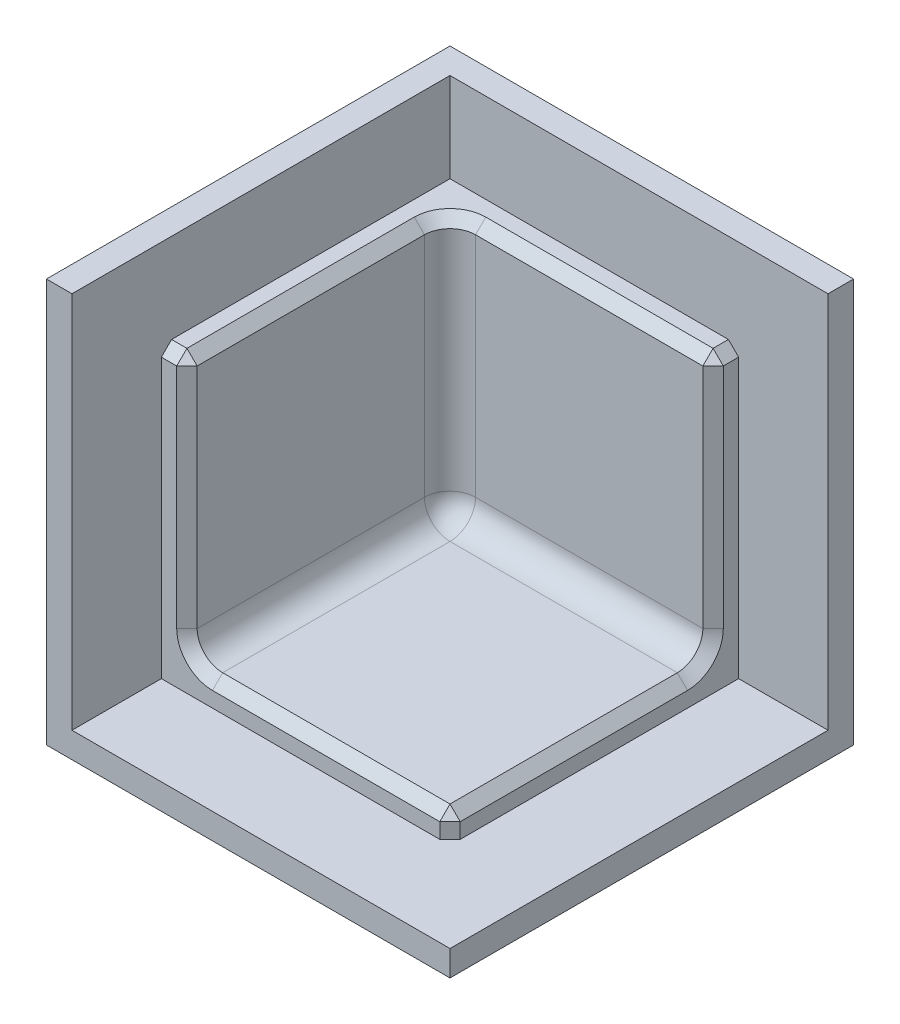
SolidWorks part; units mm, degrees
ref_plane "Plan de face" through (0, 0, 0) normal (0, 0, 1) x (1, 0, 0)
ref_plane "Plan de dessus" through (0, 0, 0) normal (0, 1, 0) x (1, 0, 0)
ref_plane "Plan de droite" through (0, 0, 0) normal (1, 0, 0) x (0, 0, -1)
sketch "Esquisse1" plane through (0, 0, 0) normal (0, 1, 0) x (1, 0, 0)
  line L1 (-7.9, 7.9) -> (7.9, 7.9)
  line L2 (-7.9, 7.9) -> (-7.9, -7.9)
  line L3 (-7.9, -7.9) -> (7.9, -7.9)
  line L4 (7.9, 7.9) -> (7.9, -7.9)
  line L5 (-7.9, 7.9) -> (7.9, -7.9) construction
  line L6 (-7.9, -7.9) -> (7.9, 7.9) construction
  point P0 (0, 0)
  dimension "D1" = 15.8
extrude "Boss.-Extru.1" add sketch "Esquisse1" along normal blind 15.8
shell "Coque1" thickness 2
sketch "Esquisse2" plane through (0, 0, 7.9) normal (0, 0, 1) x (1, 0, 0)
  line L1 (-5.9, 15.8) -> (-6.9, 15.8)
  line L2 (-5.9, 15.8) -> (-5.9, 2)
  line L4 (-6.9, 15.8) -> (-6.9, 1)
  line L5 (-5.9, 15.8) -> (-5.9, 2) construction
  line L6 (-6.9, 1) -> (7.9, 1)
  line L7 (7.9, 2) -> (7.9, 0) construction
  line L8 (7.9, 1) -> (7.9, 2)
  line L9 (7.9, 2) -> (-5.9, 2)
  dimension "D1" = 1
  dimension "D2" = 1
extrude "Enlèv. mat.-Extru.1" cut sketch "Esquisse2" against normal blind 3.5 contours L4 L6 L8 L9 L2 L1
sketch "Esquisse6" plane through (0, 15.8, 0) normal (0, 1, 0) x (1, 0, 0)
  line L0 (-5.9, -4.4) -> (-5.9, 5.9)
  line L1 (-5.9, -4.4) -> (-6.9, -4.4)
  line L2 (-6.9, -4.4) -> (-6.9, 6.9)
  line L3 (-6.9, 6.9) -> (7.9, 6.9)
  line L4 (7.9, 5.9) -> (7.9, 7.9) construction
  line L5 (7.9, 6.9) -> (7.9, 5.9)
  line L6 (7.9, 5.9) -> (-5.9, 5.9)
  dimension "D1" = 1
extrude "Enlèv. mat.-Extru.2" cut sketch "Esquisse6" against normal blind 3.5
sketch "Esquisse7" plane through (7.9, 0, 0) normal (1, 0, 0) x (0, 0, -1)
  line L0 (-4.4, 2) -> (-4.4, 1)
  line L1 (-4.4, 1) -> (6.9, 1)
  line L2 (6.9, 1) -> (6.9, 12.3)
  line L3 (6.9, 12.3) -> (5.9, 12.3)
  line L4 (5.9, 12.3) -> (6.9, 12.3) construction
  line L5 (5.9, 12.3) -> (5.9, 2)
extrude "Enlèv. mat.-Extru.3" cut sketch "Esquisse7" against normal blind 3.5 and the other way through all
fillet "Congé1" radius 1 3 edges at (-5.9, 7.15, -5.9) (-0.75, 2, -5.9) (-5.9, 2, -0.75)
chamfer "Chanfrein1" distance 0.4 angle 45 12 edges at (4.4, 7.65, -5.9) (4.4, 2, -0.25) (-0.25, 2, 4.4) (-5.9, 7.65, 4.4) (-5.9, 12.3, -0.25) (-0.25, 12.3, -5.9) (-5.6071, 2.2929, 4.4) (4.4, 2.2929, -5.6071) (-5.6071, 12.3, -5.6071) (4.4, 1.5, 4.4) (-6.4, 12.3, 4.4) (4.4, 12.3, -6.4)
